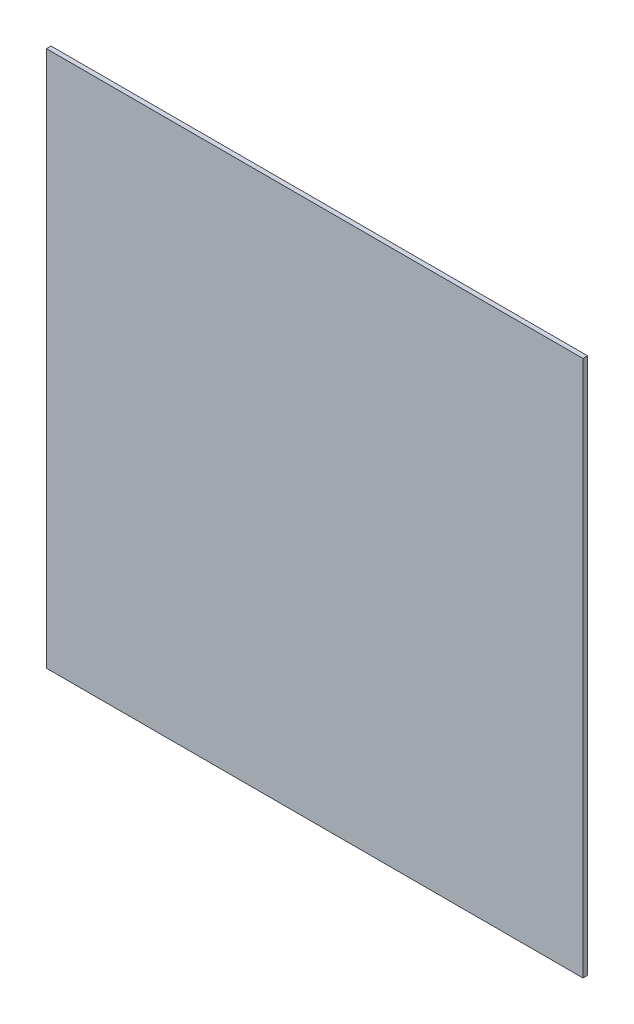
SolidWorks part; units mm, degrees
material "Al homeycomb"
ref_plane "Front Plane" through (0, 0, 0) normal (0, 0, 1) x (1, 0, 0)
ref_plane "Top Plane" through (0, 0, 0) normal (0, 1, 0) x (1, 0, 0)
ref_plane "Right Plane" through (0, 0, 0) normal (1, 0, 0) x (0, 0, -1)
sketch "Sketch1" plane through (0, 0, 0) normal (0, 0, 1) x (1, 0, 0)
  line L1 (-1450, -1450) -> (1450, -1450)
  line L2 (-1450, -1450) -> (-1450, 1450)
  line L3 (-1450, 1450) -> (1450, 1450)
  line L4 (1450, -1450) -> (1450, 1450)
  line L5 (-1450, -1450) -> (1450, 1450) construction
  line L6 (-1450, 1450) -> (1450, -1450) construction
  point P0 (0, 0)
  dimension "D1" = 2900
  dimension "D2" = 2900
extrude "Boss-Extrude1" add sketch "Sketch1" along normal blind 25
